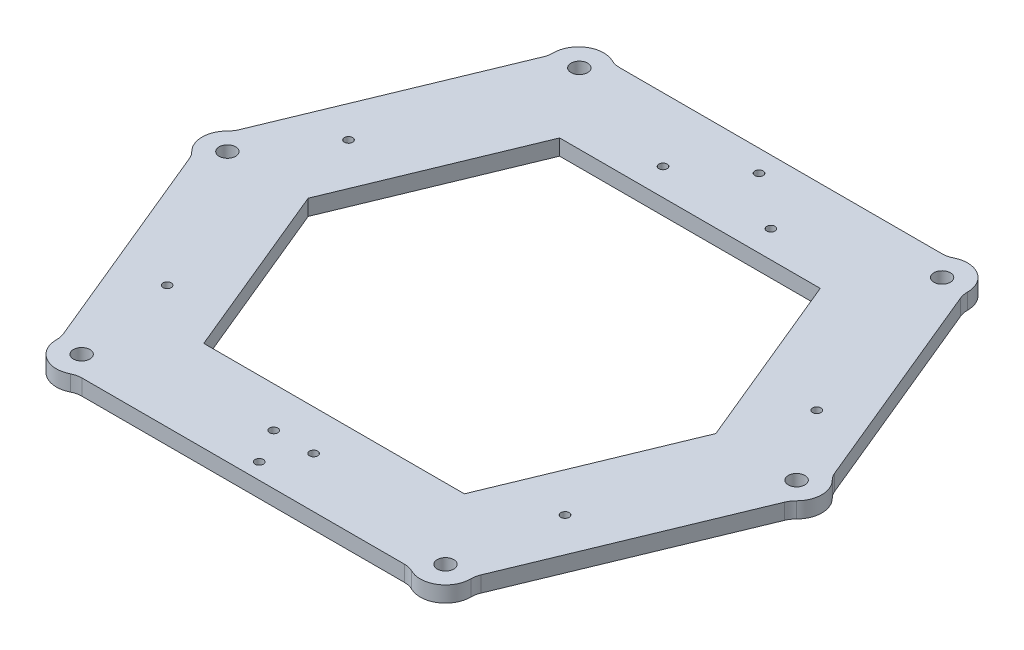
SolidWorks part; units mm, degrees
ref_plane "Front Plane" through (0, 0, 0) normal (0, 0, 1) x (1, 0, 0)
ref_plane "Top Plane" through (0, 0, 0) normal (0, 1, 0) x (1, 0, 0)
ref_plane "Right Plane" through (0, 0, 0) normal (1, 0, 0) x (0, 0, -1)
sketch "Sketch1" plane through (0, 0, 0) normal (0, 1, 0) x (1, 0, 0)
  line L0 (-54.9596, 75.057) -> (-85.979, 0) construction
  line L1 (-54.9596, -75.057) -> (54.9596, -75.057) construction
  line L2 (-54.9596, -75.057) -> (-54.9596, 75.057) construction
  line L3 (-54.9596, 75.057) -> (54.9596, 75.057) construction
  line L4 (54.9596, -75.057) -> (54.9596, 75.057) construction
  line L5 (-54.9596, -75.057) -> (54.9596, 75.057) construction
  line L6 (-54.9596, 75.057) -> (54.9596, -75.057) construction
  line L7 (-85.979, 0) -> (-54.9596, -75.057) construction
  line L8 (54.9596, 75.057) -> (85.979, 0) construction
  line L9 (85.979, 0) -> (54.9596, -75.057) construction
  line L10 (-85.979, 0) -> (85.979, 0) construction
  line L11 (-54.9596, -75.057) -> (-59.4615, -81.205) construction
  line L12 (54.9596, -75.057) -> (59.4615, -81.205) construction
  line L13 (-85.979, 0) -> (-93.0216, 0) construction
  line L14 (85.979, 0) -> (93.0216, 0) construction
  line L15 (-54.9596, 75.057) -> (-59.4615, 81.205) construction
  line L16 (54.9596, 75.057) -> (59.4615, 81.205) construction
  line L23 (-59.4615, 81.205) -> (-93.0216, 0)
  line L24 (-93.0216, 0) -> (-59.4615, -81.205)
  line L25 (-59.4615, -81.205) -> (59.4615, -81.205)
  line L26 (59.4615, -81.205) -> (93.0216, 0)
  line L27 (93.0216, 0) -> (59.4615, 81.205)
  line L28 (59.4615, 81.205) -> (-59.4615, 81.205)
  point P0 (0, 0)
  point P9 (-69.0964, 94.3632)
  point P10 (69.0964, 94.3632)
  point P13 (69.0964, 94.3632)
  point P15 (69.0964, 94.3632)
  point P16 (-60.3095, 82.3632)
  dimension "D1" = 171.958
  dimension "D2" = 186.055
  dimension "D3" = 150.114
  dimension "D4" = 7.62
extrude "Boss-Extrude2" add sketch "Sketch1" along normal blind 4.7752
sketch "Sketch4" plane through (0, 0, 0) normal (0, -1, 0) x (1, 0, 0)
  line L0 (-59.4615, 81.205) -> (59.4615, -81.205) construction
  line L1 (-59.4615, -81.205) -> (59.4615, 81.205) construction
  line L2 (-93.0216, 0) -> (93.0216, 0) construction
  line L3 (93.0216, 0) -> (59.4615, 81.205) construction
  line L4 (59.4615, 81.205) -> (-59.4615, 81.205) construction
  line L5 (-59.4615, 81.205) -> (-93.0216, 0) construction
  line L6 (-93.0216, 0) -> (-59.4615, -81.205) construction
  line L7 (-59.4615, -81.205) -> (59.4615, -81.205) construction
  line L8 (59.4615, -81.205) -> (93.0216, 0) construction
  line L9 (-39.362, 53.7557) -> (-61.578, 0)
  line L10 (-61.578, 0) -> (-39.362, -53.7557)
  line L11 (-39.362, -53.7557) -> (39.362, -53.7557)
  line L12 (39.362, -53.7557) -> (61.578, 0)
  line L13 (61.578, 0) -> (39.362, 53.7557)
  line L14 (39.362, 53.7557) -> (-39.362, 53.7557)
  point P18 (-46.3148, 63.251)
extrude "Cut-Extrude1" cut sketch "Sketch4" against normal through all both and the other way through all contours L9 L10 L11 L12 L13 L14
sketch "Sketch5" plane through (0, 0, 0) normal (0, -1, 0) x (1, 0, 0)
  line L0 (0, 0) -> (0, -81.205) construction
  line L1 (59.4615, -81.205) -> (-59.4615, -81.205) construction
  line L2 (0, 0) -> (0, 81.205) construction
  line L3 (-59.4615, 81.205) -> (59.4615, 81.205) construction
  line L4 (0, -61.924) -> (16.2941, -61.924) construction
  line L5 (0, -61.924) -> (-16.2941, -61.924) construction
  line L6 (0, 65.965) -> (6.0376, 65.965) construction
  line L7 (0, 65.965) -> (-6.0376, 65.965) construction
  line L8 (0, 65.965) -> (0, 76.379) construction
  line L9 (0, -61.924) -> (0, -74.624) construction
  line L10 (0, -21.3496) -> (-70.7306, -21.3496) construction
  line L11 (0, -21.3496) -> (70.7306, -21.3496) construction
  line L12 (0, 44.0761) -> (-60.1063, 44.0761) construction
  line L13 (0, 44.0761) -> (60.1063, 44.0761) construction
  point P17 (78.3178, -16.5018)
  point P23 (65.4626, 34.2919)
  point P24 (-60.1063, 44.0761)
  point P25 (-70.7306, -21.3496)
  point P26 (0, 0)
  dimension "D1" = 32.5882
  dimension "D2" = 12.0752
  dimension "D3" = 127.889
  dimension "D4" = 15.24
  dimension "D5" = 10.414
  dimension "D6" = 12.7
hole_wizard "Ø2.5mm Dowel Hole1" positions "3DSketch1" profile "Sketch6" hole size "Ø2.5" standard "ANSI Metric" end condition through all
sketch3d "3DSketch1"
  point P0 (-6.0376, 0, 65.965)
  point P3 (6.0376, 0, 65.965)
  point P6 (-16.2941, 0, -61.924)
  point P9 (16.2941, 0, -61.924)
  point P12 (0, 0, -74.624)
  point P14 (0, 0, 76.379)
  point P21 (-60.1063, 0, 44.0761)
  point P23 (-70.7306, 0, -21.3496)
  point P25 (70.7306, 0, -21.3496)
  point P27 (60.1063, 0, 44.0761)
  point P30 (-60.1063, 0, 44.0761)
  point P32 (-70.7306, 0, -21.3496)
  point P34 (70.7306, 0, -21.3496)
  point P36 (60.1063, 0, 44.0761)
sketch "Sketch6" plane through (-6.0376, 0, 65.965) normal (1, 0, 0) x (0, 0, -1)
  line L0 (0, 0) -> (0, 4.7752)
  line L1 (0, 4.7752) -> (1.25, 4.7752)
  line L2 (1.25, 4.7752) -> (1.25, 0.025)
  line L3 (1.25, 0.025) -> (1.275, 0)
  line L5 (1.275, 0) -> (0, 0)
  line L6 (-1.25, 0.025) -> (-1.275, 0) construction
  line L11 (0, -6.35) -> (0, 107.95) construction
  dimension "Thru Hole Dia." = 2.5
  dimension "Thru Hole Depth" = 4.7752
  dimension "Near C'Sink Dia." = 2.55
  dimension "Near C'Sink Angle" = 90
sketch "Sketch7" plane through (0, 0, 0) normal (0, -1, 0) x (1, 0, 0)
  circle A0 centre (-54.9596, 75.057) radius 7.62
  circle A1 centre (54.9596, 75.057) radius 7.62
  circle A2 centre (85.979, 0) radius 7.62
  circle A3 centre (54.9596, -75.057) radius 7.62
  circle A4 centre (-54.9596, -75.057) radius 7.62
  circle A5 centre (-85.979, 0) radius 7.62
  dimension "D1" = 15.24
extrude "Boss-Extrude3" add sketch "Sketch7" against normal blind 4.7752
fillet "Fillet1" radius 6.35 12 edges at (50.4578, 2.3876, -81.205) (-50.4578, 2.3876, -81.205) (90.4808, 2.3876, -6.148) (62.4883, 2.3876, -73.8809) (90.4808, 2.3876, 6.148) (62.4883, 2.3876, 73.8809) (50.4578, 2.3876, 81.205) (-50.4578, 2.3876, 81.205) (-62.4883, 2.3876, 73.8809) (-90.4808, 2.3876, 6.148) (-90.4808, 2.3876, -6.148) (-62.4883, 2.3876, -73.8809)
hole_wizard "Ø5.0mm Dowel Hole1" positions "3DSketch6" profile "Sketch12" hole size "Ø5.0" standard "ANSI Metric"
sketch3d "3DSketch6"
  line L0 (85.979, 0, 0) -> (54.9596, 0, 75.057) construction
  line L1 (-85.979, 0, 0) -> (85.979, 0, 0) construction
  line L2 (-54.9596, 0, 75.057) -> (54.9596, 0, -75.057) construction
  line L3 (-54.9596, 0, -75.057) -> (54.9596, 0, -75.057) construction
  point P0 (54.9596, 0, -75.057)
  point P3 (54.9217, 0, -75.0051)
  point P5 (-54.7155, 0, -75.057)
  point P7 (-85.979, 0, 0)
  point P9 (85.979, 0, 0)
  point P11 (54.9596, 0, 75.057)
  point P13 (-54.9596, 0, 75.057)
  point P16 (54.9596, 0, 75.057)
  point P18 (-54.9596, 0, 75.057)
  point P20 (-85.979, 0, 0)
  point P22 (85.9273, 0, 0.1252)
  point P25 (83.9153, 0, 4.9936)
  point P26 (85.979, 0, 0)
  point P29 (0, 0, 0)
  point P30 (51.647, 0, -70.533)
  point P33 (54.9596, 0, -74.9006)
  point P34 (-54.7155, 0, -75.057)
  point P37 (52.1096, 0, -71.1648)
  point P38 (0, 0, 0)
  point P39 (54.9596, 0, -75.0051)
sketch "Sketch12" plane through (-54.9596, 0, 75.057) normal (1, 0, 0) x (0, 0, -1)
  line L0 (0, 0) -> (0, 4.7752)
  line L1 (0, 4.7752) -> (2.5, 4.7752)
  line L2 (2.5, 4.7752) -> (2.5, 0.025)
  line L3 (2.5, 0.025) -> (2.525, 0)
  line L5 (2.525, 0) -> (0, 0)
  line L6 (-2.5, 0.025) -> (-2.525, 0) construction
  line L11 (0, -6.35) -> (0, 107.95) construction
  dimension "Thru Hole Dia." = 5
  dimension "Thru Hole Depth" = 4.7752
  dimension "Near C'Sink Dia." = 5.05
  dimension "Near C'Sink Angle" = 90
